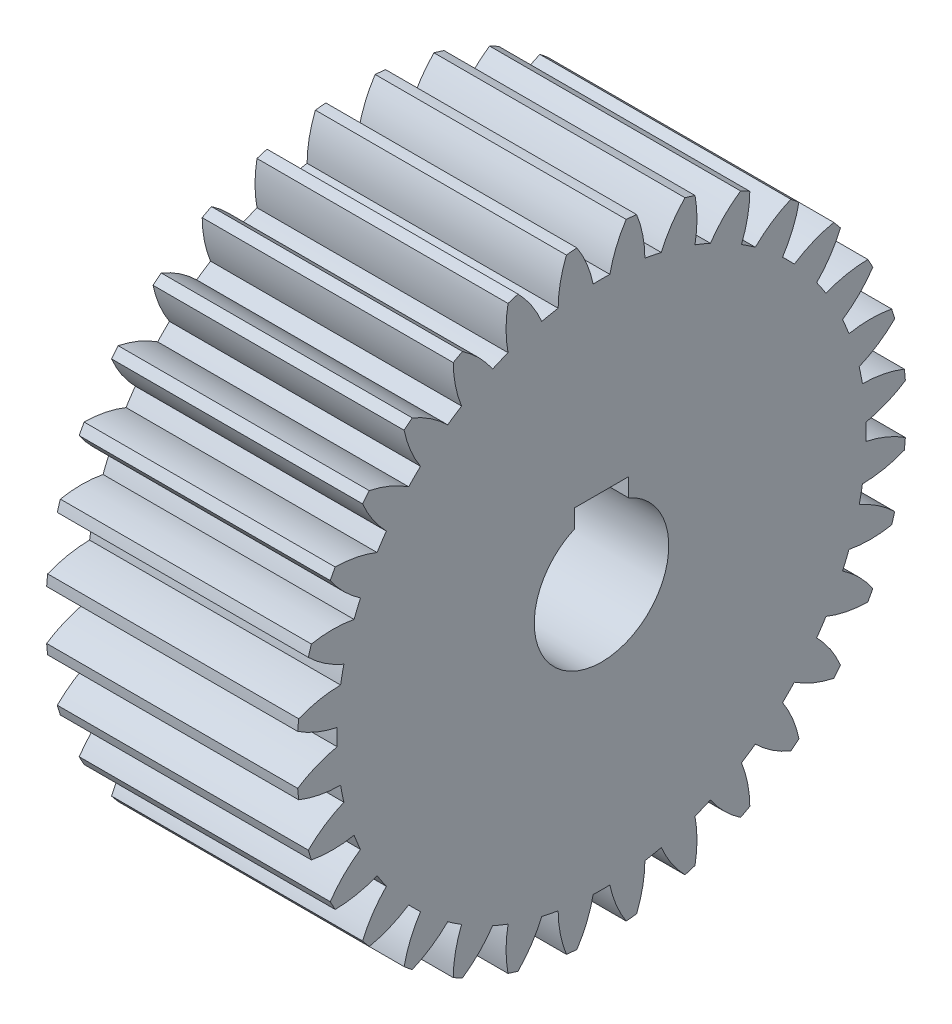
SolidWorks part; units mm, degrees
ref_plane "Plane1" through (0, 0, 0) normal (0, 0, 1) x (1, 0, 0)
ref_plane "Plane2" through (0, 0, 0) normal (0, 1, 0) x (1, 0, 0)
ref_plane "Plane3" through (0, 0, 0) normal (1, 0, 0) x (0, 0, -1)
sketch "HoldingSke" plane through (0, 0, 0) normal (0, 1, 0) x (1, 0, 0)
  line L0 (0, 0) -> (129.2425, -80.7597)
  line L1 (-15, 0) -> (100, 0) construction
  line L2 (0, 0) -> (-2.1039, 2.3779)
  line L3 (0, 0) -> (-11.863, 4.5341)
  line L4 (0, 0) -> (7.3237, 4.5764)
  line L5 (0, 0) -> (-47.5972, -17.7524)
  line L6 (0, 0) -> (-49.1299, -33.1481)
  line L7 (-2.1039, 2.3779) -> (10.6532, 60.2553)
  line L8 (-76.2, 54.61) -> (-41.4782, 54.61)
  line L9 (-71.009, 38.7566) -> (-53.1078, 45.2721)
  line L10 (-76.2, 71.12) -> (104.1128, 71.12)
  line L11 (0, 0) -> (-59.2667, 0)
  line L12 (-76.2, 101.6) -> (-76.0298, 101.6)
  line L13 (24.9733, 27.94) -> (52.9518, 28.4284)
  line L14 (24.9733, 27.94) -> (24.9746, 27.94)
  line L15 (24.9733, 27.94) -> (100.4006, 29.5858)
  circle A0 centre (0, 0) radius 15.875
  circle A1 centre (0, 0) radius 38.1
  circle A2 centre (0, 0) radius 38.1
  circle A3 centre (0, 0) radius 15.875
  dimension "MHD" = 76.2
  dimension "Hub_dia" = 76.2
  dimension "Bore" = 31.75
  dimension "MBD" = 31.75
  dimension "Num_teeth" = 32
  dimension "Pitch" = 152.4
  dimension "Overall_len" = 50.8
  dimension "Show_teeth" = 32
  dimension "Thickness" = 59.2667
  dimension "OAL" = 59.2667
  dimension "T_dim" = 34.7218
  dimension "Ap" = 20
  dimension "H" = 19.05
  dimension "Pitch_radius" = 180.3128
  dimension "Width" = 59.2667
  dimension "Backlash" = 0.1702
  dimension "Addendum_fac" = 1
  dimension "Dedendum_fac" = 1.25
  dimension "Clearance_fac" = 0.25
  dimension "Dedendum_add" = 0.0013
sketch "BasProSke" plane through (0, 0, 0) normal (0, 1, 0) x (1, 0, 0)
  line L0 (-10, 0) -> (60, 0) construction
  line L1 (0, 0) -> (0, 71.9667)
  line L2 (0, 0) -> (59.2667, 0)
  line L3 (59.2667, 0) -> (59.2667, 71.9667)
  line L4 (59.2667, 71.9667) -> (0, 71.9667)
  dimension "Thickness" = 59.2667
  dimension "Diameter" = 143.9333
revolve "Base-Revolve" add sketch "BasProSke" angle 360 about L0
sketch "TooCutSke" plane through (0, 0, 0) normal (1, 0, 0) x (0, 0, -1)
  line L1 (0, 0) -> (0, 107) construction
  line L2 (0, 0) -> (-3.6213, 67.6365) construction
  line L3 (0, 0) -> (-13.2648, 134.6798) construction
  line L4 (-3.6213, 67.6365) -> (-6.6324, 67.3399) construction
  arc A0 (1.9716, 62.4093) -> (-1.9716, 62.4093) centre (0, 0) ccw
  arc A1 (5.8363, 71.7551) -> (-5.8363, 71.7551) centre (0, 0) ccw
  circle A2 centre (0, 0) radius 67.7333 construction
  circle A3 centre (0, 0) radius 63.6485 construction
  arc A4 (-1.9716, 62.4093) -> (-5.8363, 71.7551) centre (-28.5011, 56.9106) ccw
  arc A5 (5.8363, 71.7551) -> (1.9716, 62.4093) centre (28.5011, 56.9106) ccw
  dimension "Root_dia" = 124.8808
  dimension "Overcut_dia" = 143.9841
  dimension "Pitch_dia" = 135.4667
  dimension "Base_dia" = 127.297
  dimension "Flank_rad" = 27.0933
  dimension "Half_ang" = 5.625
  dimension "Half_CT" = 3.0257
extrude "ToothCut" cut sketch "TooCutSke" along normal through all
fillet "Breaks" [suppressed] radius 0.0847
fillet "RootFillets" [suppressed] radius 1.0596
pattern_circular "TeethCuts" count 32 every 11.25 about axis through (-10, 0, 0) along (1, 0, 0) of "ToothCut", "RootFillets", "Breaks"
sketch "HubNeaOneSke" plane through (0, 0, 0) normal (-1, 0, 0) x (0, 0, 1)
  circle A0 centre (0, 0) radius 38.1
  dimension "Diameter" = 76.2
extrude "HubNearOne" [suppressed] add sketch "HubNeaOneSke" along normal blind 12.7001
sketch "HubNeaBotSke" plane through (0, 0, 0) normal (-1, 0, 0) x (0, 0, 1)
  circle A0 centre (0, 0) radius 38.1
  dimension "Diameter" = 76.2
extrude "HubNearBoth" [suppressed] add sketch "HubNeaBotSke" along normal blind 6.35
ref_plane "FarPln" through (59.2667, 0, 0) normal (1, 0, 0) x (0, 0, -1)
sketch "HubFarSke" plane through (59.2667, 0, 0) normal (1, 0, 0) x (0, 0, -1)
  circle A0 centre (0, 0) radius 38.1
  dimension "Diameter" = 76.2
extrude "HubFar" [suppressed] add sketch "HubFarSke" along normal blind 6.35
sketch "BorSke" plane through (0, 0, 0) normal (1, 0, 0) x (0, 0, -1)
  circle A0 centre (0, 0) radius 15.875
  dimension "Diameter" = 31.75
extrude "Bore" cut sketch "BorSke" along normal mid plane 118.5334
sketch "KeySke" plane through (0, 0, 0) normal (1, 0, 0) x (0, 0, -1)
  line L0 (-6.35, 0) -> (-6.35, 18.8468)
  line L1 (-6.35, 18.8468) -> (6.35, 18.8468)
  line L2 (6.35, 18.8468) -> (6.35, 0)
  line L3 (0, 0) -> (0, 34) construction
  line L4 (-6.35, 0) -> (6.35, 0)
  dimension "Offset" = 18.8468
  dimension "Width" = 12.7
extrude "Keyway" cut sketch "KeySke" along normal mid plane 118.5334
pattern_circular "Keyway2" [suppressed] count 2 every 90 about axis through (-10, 0, 0) along (1, 0, 0)
equation "' \"Pitch@HoldingSke\" = 4"
equation "' \"Num_teeth@HoldingSke\" = 12"
equation "' \"Ap@HoldingSke\" =  20"
equation "' \"Ap@HoldingSke\" = 20"
equation "' \"Width@HoldingSke\" = 0.5"
equation "' \"Hub_dia@HoldingSke\"= 1"
equation "' \"Hub_dia@HoldingSke\" = 1"
equation "' \"Overall_len@HoldingSke\" = 1.0"
equation "' \"Bore@HoldingSke\" = 0.75"
equation "' \"T_dim@HoldingSke\" = 0.85"
equation "' \"Width@KeySke\" = 0.25"
equation "' \"Show_teeth@HoldingSke\" = 13"
equation "' \"Backlash@HoldingSke\" = 0.009"
equation "' \"Addendum_fac@HoldingSke\" = 1.0"
equation "' \"Dedendum_fac@HoldingSke\" = 1.25"
equation "' \"Dedendum_add@HoldingSke\" = 0.00005"
equation "' \"Clearance_fac@HoldingSke\" = 0.25"
equation "' \"Pitch@HoldingSke\" = 0.5"
equation "' \"Num_teeth@HoldingSke\" = 23"
equation "' \"Show_teeth@HoldingSke\" = 23"
equation "' \"Backlash@HoldingSke\" = 0.0375"
equation "\"Overcut_dia@TooCutSke\" = (\"Num_teeth@HoldingSke\" + 2 * \"Addendum_fac@HoldingSke\") / \"Pitch@HoldingSke\" + 0.002"
equation "\"Pitch_dia@TooCutSke\" = \"Num_teeth@HoldingSke\" / \"Pitch@HoldingSke\""
equation "\"Base_dia@TooCutSke\" = \"Num_teeth@HoldingSke\" / \"Pitch@HoldingSke\" * cos((\"Ap@HoldingSke\"  * 3.14159265 / 180))"
equation "\"Root_dia@TooCutSke\" = (\"Num_teeth@HoldingSke\" + 2) / \"Pitch@HoldingSke\" - 2 * (\"Addendum_fac@HoldingSke\" + \"Dedendum_fac@HoldingSke\") / \"Pitch@HoldingSke\" - \"Dedendum_add@HoldingSke\" * 2"
equation "\"Half_ang@TooCutSke\" = 180 / \"Num_teeth@HoldingSke\""
equation "\"Half_CT@TooCutSke\" = \"Num_teeth@HoldingSke\" / \"Pitch@HoldingSke\" * sin((3.14159265 / 2 / \"Num_teeth@HoldingSke\")) / 2 - 7 * \"Backlash@HoldingSke\" / 4"
equation "\"Flank_rad@TooCutSke\" = \"Num_teeth@HoldingSke\" / \"Pitch@HoldingSke\" / 5"
equation "\"Radius@RootFillets\" = \"Clearance_fac@HoldingSke\" / \"Pitch@HoldingSke\" + \"Dedendum_add@HoldingSke\""
equation "\"Break_rad@Breaks\" = 0.02 / \"Pitch@HoldingSke\""
equation "\"Thickness@HoldingSke\" = \"Width@HoldingSke\""
equation "\"OAL@HoldingSke\" = \"Thickness@HoldingSke\""
equation "\"MHD@HoldingSke\" = (\"Num_teeth@HoldingSke\" + 2) / \"Pitch@HoldingSke\" - 2 * (\"Addendum_fac@HoldingSke\" + \"Dedendum_fac@HoldingSke\")  / \"Pitch@HoldingSke\" - \"Dedendum_add@HoldingSke\" * 2"
equation "\"MBD@HoldingSke\" = (\"Num_teeth@HoldingSke\" + 2) / \"Pitch@HoldingSke\" - 2 * (\"Addendum_fac@HoldingSke\" + \"Dedendum_fac@HoldingSke\")  / \"Pitch@HoldingSke\" - \"Dedendum_add@HoldingSke\" * 2 - 0.002"
equation "\"MHD@HoldingSke\" = ((sgn( \"MHD@HoldingSke\" - \"Hub_dia@HoldingSke\" )-1)*( \"MHD@HoldingSke\" - \"Hub_dia@HoldingSke\" ))/-2+ \"Hub_dia@HoldingSke\""
equation "\"MBD@HoldingSke\" = ((sgn( \"MBD@HoldingSke\" - \"Bore@HoldingSke\" )-1)*( \"MBD@HoldingSke\" - \"Bore@HoldingSke\" ))/-2+ \"Bore@HoldingSke\""
equation "\"OAL@HoldingSke\" = ((sgn( \"OAL@HoldingSke\" - \"Overall_len@HoldingSke\" )+1)*( \"OAL@HoldingSke\" - \"Overall_len@HoldingSke\" ))/2 + \"Overall_len@HoldingSke\" + 0.000002"
equation "\"Num_teeth@TeethCuts\" = int( \"Show_teeth@HoldingSke\" ) + 1"
equation "\"Num_teeth@TeethCuts\" = ((sgn( \"Num_teeth@TeethCuts\" - \"Num_teeth@HoldingSke\" )-1)*( \"Num_teeth@TeethCuts\" - \"Num_teeth@HoldingSke\" ))/-2+ \"Num_teeth@HoldingSke\""
equation "\"Num_teeth@TeethCuts\" = ((sgn( \"Num_teeth@TeethCuts\" - 2.0)+1)*( \"Num_teeth@TeethCuts\" - 2.0))/2 +2.0"
equation "\"Angle@TeethCuts\" = 360.0 / \"Num_teeth@HoldingSke\""
equation "\"Diameter@BasProSke\" = (\"Num_teeth@HoldingSke\" + 2 * \"Addendum_fac@HoldingSke\") / \"Pitch@HoldingSke\""
equation "\"Thickness@BasProSke\"  = \"Thickness@HoldingSke\""
equation "' \"Fillet_rad@BasProSke\" =  \"Thickness@HoldingSke\" * 0.05"
equation "' \"Fillet_rad@BasProSke\" = \"Thickness@HoldingSke\" * 0.05"
equation "\"MHD@HoldingSke\" = ((sgn( \"MHD@HoldingSke\" - \"Root_dia@TooCutSke\" )-1)*( \"MHD@HoldingSke\" - \"Root_dia@TooCutSke\" ))/-2+ \"Root_dia@TooCutSke\""
equation "\"Diameter@HubNeaOneSke\" = \"MHD@HoldingSke\""
equation "\"Length@HubNearOne\" = \"OAL@HoldingSke\" - \"Thickness@BasProSke\""
equation "\"Diameter@HubNeaBotSke\" = \"MHD@HoldingSke\""
equation "\"Length@HubNearBoth\" = ( \"OAL@HoldingSke\" - \"Thickness@BasProSke\" ) / 2.0"
equation "\"Thickness@FarPln\" = \"Thickness@BasProSke\""
equation "\"Diameter@HubFarSke\" = \"MHD@HoldingSke\""
equation "\"Length@HubFar\" = ( \"OAL@HoldingSke\" - \"Thickness@BasProSke\" ) / 2.0"
equation "\"Diameter@BorSke\" = \"MBD@HoldingSke\""
equation "\"D1@Bore\" = \"OAL@HoldingSke\" * 2.0"
equation "\"D1@Keyway\" = \"OAL@HoldingSke\" * 2.0"
equation "\"Offset@KeySke\" = \"T_dim@HoldingSke\" - \"MBD@HoldingSke\" / 2.0"
